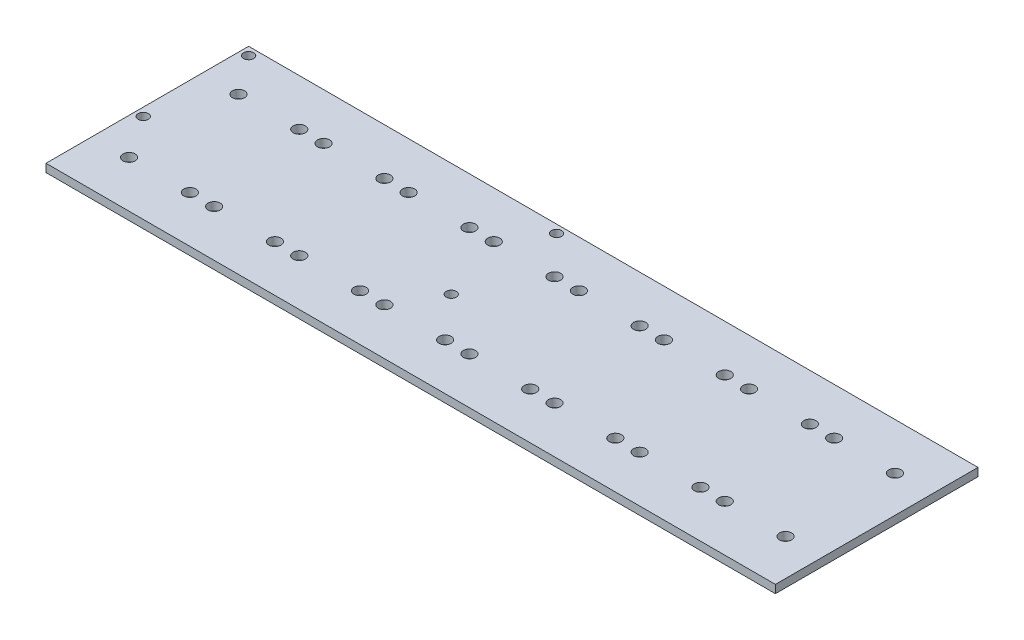
SolidWorks part; units mm, degrees
ref_plane "前视基准面" through (0, 0, 0) normal (0, 0, 1) x (1, 0, 0)
ref_plane "上视基准面" through (0, 0, 0) normal (0, 1, 0) x (1, 0, 0)
ref_plane "右视基准面" through (0, 0, 0) normal (1, 0, 0) x (0, 0, -1)
sketch "草图1" plane through (0, 0, 0) normal (0, 1, 0) x (1, 0, 0)
  line L0 (9, 0) -> (9, -50) construction
  line L1 (0, 0) -> (180, 0)
  line L2 (0, 0) -> (0, -50)
  line L3 (0, -50) -> (180, -50)
  line L4 (180, 0) -> (180, -50)
  line L5 (0, -11.5) -> (180, -11.5) construction
  line L6 (80, 0) -> (80, -50) construction
  line L7 (0, -30) -> (80, -30) construction
  circle A1 centre (9, -11.5) radius 1.5
  circle A2 centre (9, -38.5) radius 1.5
  circle A3 centre (24, -11.5) radius 1.5
  circle A4 centre (24, -38.5) radius 1.5
  circle A5 centre (30, -38.5) radius 1.5
  circle A6 centre (45, -38.5) radius 1.5
  circle A7 centre (45, -11.5) radius 1.5
  circle A8 centre (30, -11.5) radius 1.5
  circle A9 centre (51, -38.5) radius 1.5
  circle A10 centre (66, -38.5) radius 1.5
  circle A11 centre (66, -11.5) radius 1.5
  circle A12 centre (51, -11.5) radius 1.5
  circle A13 centre (72, -38.5) radius 1.5
  circle A14 centre (87, -38.5) radius 1.5
  circle A15 centre (87, -11.5) radius 1.5
  circle A16 centre (72, -11.5) radius 1.5
  circle A17 centre (93, -38.5) radius 1.5
  circle A18 centre (108, -38.5) radius 1.5
  circle A19 centre (108, -11.5) radius 1.5
  circle A20 centre (93, -11.5) radius 1.5
  circle A21 centre (114, -38.5) radius 1.5
  circle A22 centre (129, -38.5) radius 1.5
  circle A23 centre (129, -11.5) radius 1.5
  circle A24 centre (114, -11.5) radius 1.5
  circle A25 centre (135, -38.5) radius 1.5
  circle A26 centre (150, -38.5) radius 1.5
  circle A27 centre (150, -11.5) radius 1.5
  circle A28 centre (135, -11.5) radius 1.5
  circle A29 centre (156, -38.5) radius 1.5
  circle A30 centre (171, -38.5) radius 1.5
  circle A31 centre (171, -11.5) radius 1.5
  circle A32 centre (156, -11.5) radius 1.5
  circle A33 centre (2, -2) radius 1.25
  circle A34 centre (78, -2) radius 1.25
  circle A35 centre (2, -28) radius 1.25
  circle A36 centre (78, -28) radius 1.25
  dimension "D3" = 11.5
  dimension "D5" = 3
  dimension "D7" = 27
  dimension "D12" = 2.5
  dimension "D1" = 180
  dimension "D2" = 50
  dimension "D4" = 9
  dimension "D10" = 80
  dimension "D11" = 30
  dimension "D13" = 2
  dimension "D14" = 2
  dimension "D6" = 2
  dimension "D8" = 2
  dimension "D9" = 8
  dimension "D15" = 2
  dimension "D16" = 2
extrude "凸台-拉伸1" add sketch "草图1" along normal blind 2
